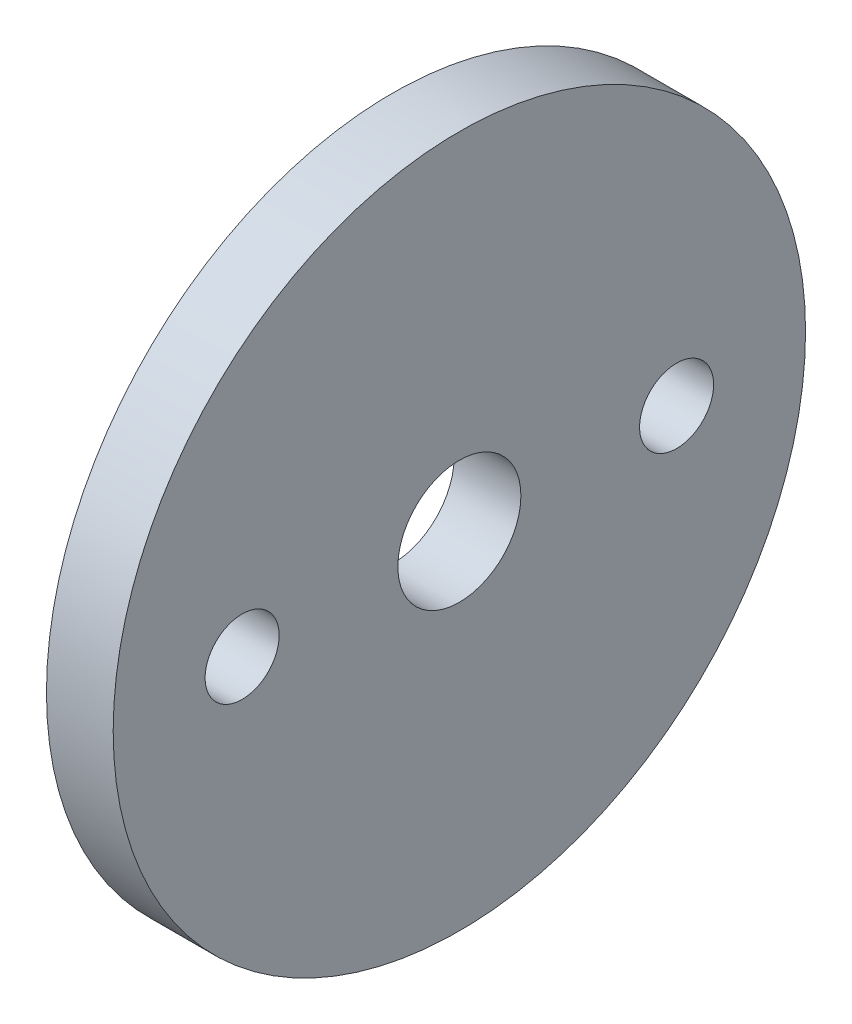
SolidWorks part; units mm, degrees
material "Wildman Fiberglass"
ref_plane "Front Plane" through (0, 0, 0) normal (0, 0, 1) x (1, 0, 0)
ref_plane "Top Plane" through (0, 0, 0) normal (0, 1, 0) x (1, 0, 0)
ref_plane "Right Plane" through (0, 0, 0) normal (1, 0, 0) x (0, 0, -1)
sketch "Sketch1" plane through (0, 0, 0) normal (1, 0, 0) x (0, 0, -1)
  circle A0 centre (0, 0) radius 12.6492
  dimension "D1" = 25.2984
extrude "Boss-Extrude1" add sketch "Sketch1" along normal blind 2.4384
hole_wizard "#8 Threaded Rod Clearance" positions "Sketch3" profile "Sketch4" hole size "#8" standard "ANSI Inch" end condition through all
sketch "Sketch3" plane through (2.4384, 0, 0) normal (1, 0, 0) x (0, 0, -1)
  point P0 (0, 0)
sketch "Sketch4" plane through (2.4384, 0, 0) normal (0, 1, 0) x (0, 0, -1)
  line L0 (0, 0) -> (0, 2.4384)
  line L1 (0, 2.4384) -> (2.2479, 2.4384)
  line L2 (2.2479, 2.4384) -> (2.2479, 0)
  line L5 (2.2479, 0) -> (0, 0)
  line L11 (0, -6.35) -> (0, 107.95) construction
  dimension "Thru Hole Dia." = 4.4958
  dimension "Thru Hole Depth" = 2.4384
hole_wizard "Ejection Charge Passthrough" positions "Sketch5" profile "Sketch6" hole size "#36" standard "ANSI Inch" end condition through all
sketch "Sketch5" plane through (2.4384, 0, 0) normal (1, 0, 0) x (0, 0, -1)
  line L0 (-7.9375, 0) -> (7.9375, 0) construction
  point P0 (-7.9375, 0)
  point P2 (7.9375, 0)
  point P7 (0, 0)
  dimension "D1" = 15.875
sketch "Sketch6" plane through (2.4384, 0, 7.9375) normal (0, 1, 0) x (0, 0, -1)
  line L0 (0, 0) -> (0, 2.4384)
  line L1 (0, 2.4384) -> (1.3525, 2.4384)
  line L2 (1.3525, 2.4384) -> (1.3525, 0)
  line L5 (1.3525, 0) -> (0, 0)
  line L11 (0, -6.35) -> (0, 107.95) construction
  dimension "Thru Hole Dia." = 2.7051
  dimension "Thru Hole Depth" = 2.4384
